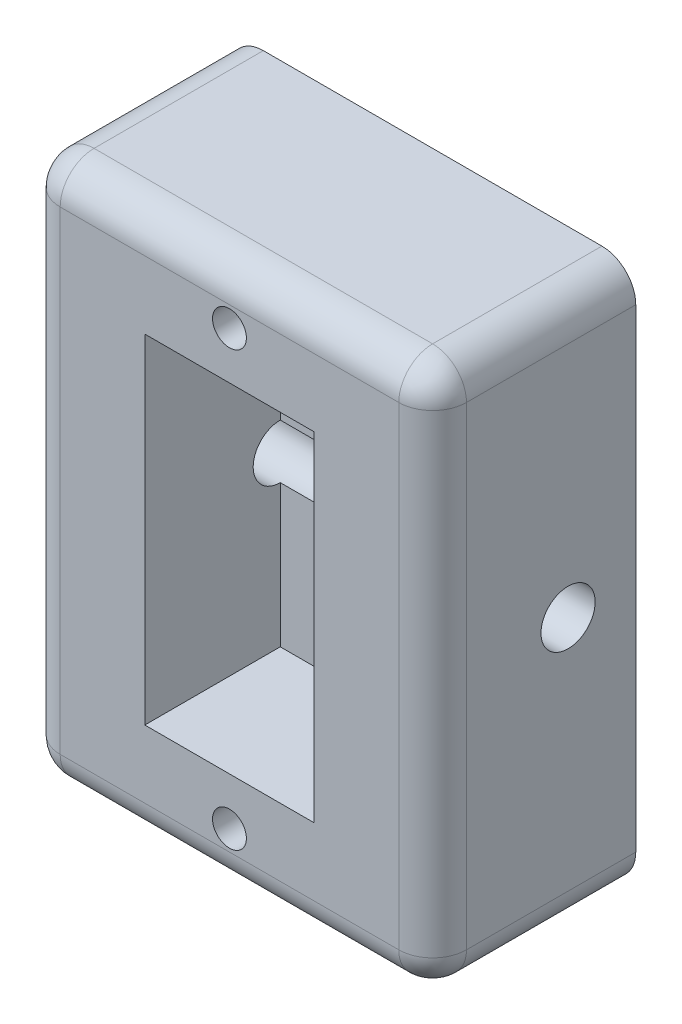
SolidWorks part; units mm, degrees
ref_plane "Front Plane" through (0, 0, 0) normal (0, 0, 1) x (1, 0, 0)
ref_plane "Top Plane" through (0, 0, 0) normal (0, 1, 0) x (1, 0, 0)
ref_plane "Right Plane" through (0, 0, 0) normal (1, 0, 0) x (0, 0, -1)
sketch "Sketch1" plane through (0, 0, 0) normal (0, 0, 1) x (1, 0, 0)
  line L1 (-30, -40) -> (30, -40)
  line L2 (-30, -40) -> (-30, 40)
  line L3 (-30, 40) -> (30, 40)
  line L4 (30, -40) -> (30, 40)
  line L5 (-30, -40) -> (30, 40) construction
  line L6 (-30, 40) -> (30, -40) construction
  point P0 (0, 0)
extrude "Boss-Extrude1" add sketch "Sketch1" against normal blind 30
sketch "Sketch2" plane through (0, 0, 0) normal (0, 0, 1) x (1, 0, 0)
  line L1 (-12.5, -25) -> (12.5, -25)
  line L2 (-12.5, -25) -> (-12.5, 25)
  line L3 (-12.5, 25) -> (12.5, 25)
  line L4 (12.5, -25) -> (12.5, 25)
  line L5 (-12.5, -25) -> (12.5, 25) construction
  line L6 (-12.5, 25) -> (12.5, -25) construction
  point P0 (0, 0)
extrude "Cut-Extrude1" cut sketch "Sketch2" against normal blind 20
sketch "Sketch4" plane through (0, 0, 0) normal (1, 0, 0) x (0, 0, -1)
  line L0 (0, 0) -> (30, 0) construction
  line L1 (30, -40) -> (30, 40) construction
  line L2 (15, -40) -> (15, 0) construction
  line L3 (30, 0) -> (20, 0) construction
  line L4 (30, -40) -> (0, -40) construction
  circle A0 centre (20, 0) radius 4
extrude "Cut-Extrude3" cut sketch "Sketch4" against normal through all both and the other way through all
sketch "Sketch5" plane through (0, 0, 0) normal (0, 0, 1) x (1, 0, 0)
  line L0 (0, 40) -> (0, 32) construction
  line L1 (30, 40) -> (-30, 40) construction
  line L2 (0, -40) -> (0, -32) construction
  line L3 (-30, -40) -> (30, -40) construction
  circle A0 centre (0, 32) radius 2.5
  circle A1 centre (0, -32) radius 2.5
extrude "Cut-Extrude4" cut sketch "Sketch5" against normal blind 29 and the other way through all
fillet "Fillet1" radius 5 8 edges at (30, 40, -15) (-30, 40, -15) (-30, -40, -15) (30, -40, -15) (0, -40, 0) (30, 0, 0) (0, 40, 0) (-30, 0, 0)
